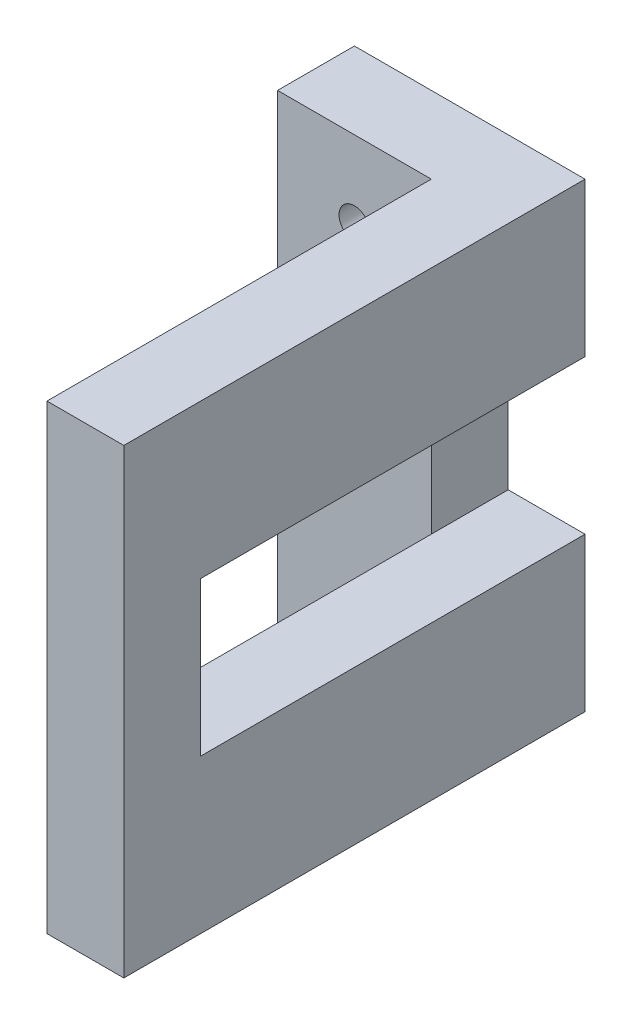
SolidWorks part; units mm, degrees
ref_plane "Front Plane" through (0, 0, 0) normal (0, 0, 1) x (1, 0, 0)
ref_plane "Top Plane" through (0, 0, 0) normal (0, 1, 0) x (1, 0, 0)
ref_plane "Right Plane" through (0, 0, 0) normal (1, 0, 0) x (0, 0, -1)
sketch "Sketch1" plane through (0, 0, 0) normal (0, 0, 1) x (1, 0, 0)
  line L1 (3.0702, 32.2807) -> (33.0702, 32.2807)
  line L2 (3.0702, 32.2807) -> (3.0702, -27.7193)
  line L3 (3.0702, -27.7193) -> (33.0702, -27.7193)
  line L4 (33.0702, 32.2807) -> (33.0702, -27.7193)
  dimension "D1" = 60
  dimension "D2" = 30
extrude "Boss-Extrude1" add sketch "Sketch1" along normal blind 10
sketch "Sketch2" plane through (0, 0, 10) normal (0, 0, 1) x (1, 0, 0)
  line L0 (3.0702, -27.7193) -> (33.0702, -27.7193) construction
  line L1 (33.0702, 32.2807) -> (23.0702, 32.2807)
  line L2 (33.0702, 32.2807) -> (33.0702, -27.7193)
  line L3 (33.0702, -27.7193) -> (23.0702, -27.7193)
  line L4 (23.0702, 32.2807) -> (23.0702, -27.7193)
  dimension "D1" = 10
extrude "Boss-Extrude2" add sketch "Sketch2" along normal blind 50
sketch "Sketch3" plane through (0, 0, 10) normal (0, 0, 1) x (1, 0, 0)
  line L0 (23.0702, 32.2807) -> (3.0702, 32.2807) construction
  line L1 (3.0702, 32.2807) -> (3.0702, -27.7193) construction
  circle A0 centre (13.0702, 22.2807) radius 2
  circle A1 centre (13.0702, 2.2807) radius 2
  dimension "D1" = 4
  dimension "D2" = 4
  dimension "D3" = 20
  dimension "D4" = 10
  dimension "D5" = 10
  dimension "D6" = 10
extrude "Cut-Extrude1" cut sketch "Sketch3" against normal blind 50
sketch "Sketch4" plane through (0, 0, 0) normal (0, 0, -1) x (-1, 0, 0)
  line L0 (-33.0702, -27.7193) -> (-33.0702, 32.2807) construction
  line L1 (-33.0702, 12.2807) -> (-23.0702, 12.2807)
  line L2 (-33.0702, 12.2807) -> (-33.0702, -7.7193)
  line L3 (-33.0702, -7.7193) -> (-23.0702, -7.7193)
  line L4 (-23.0702, 12.2807) -> (-23.0702, -7.7193)
  line L5 (-33.0702, 32.2807) -> (-3.0702, 32.2807) construction
  dimension "D1" = 10
  dimension "D2" = 20
  dimension "D3" = 20
extrude "Cut-Extrude2" cut sketch "Sketch4" against normal blind 50
